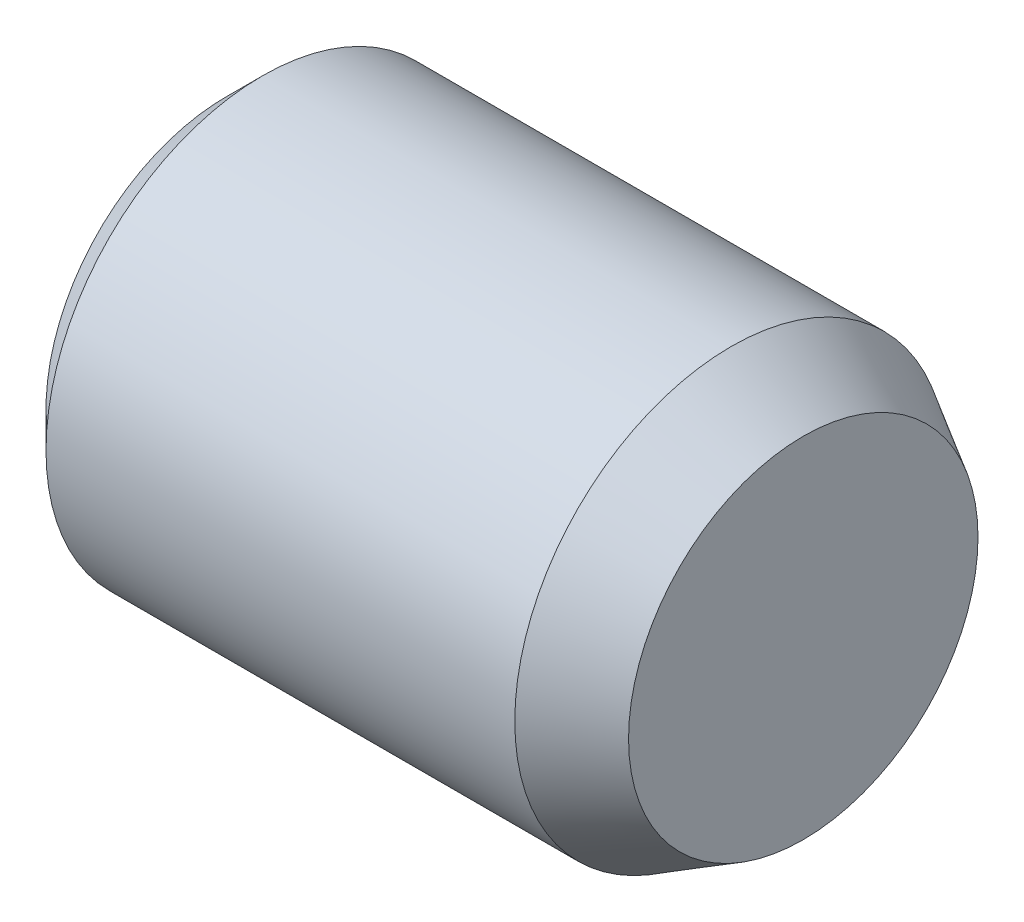
SolidWorks part; units mm, degrees
ref_plane "Přední rovina" through (0, 0, 0) normal (0, 0, 1) x (1, 0, 0)
ref_plane "Vrchní rovina" through (0, 0, 0) normal (0, 1, 0) x (1, 0, 0)
ref_plane "Pravá rovina" through (0, 0, 0) normal (1, 0, 0) x (0, 0, -1)
sketch "Skica1" plane through (0, 0, 0) normal (0, 1, 0) x (1, 0, 0)
  line L0 (0, 0) -> (0, 2.5)
  line L1 (0, 2.5) -> (0.5, 3)
  line L2 (0.5, 3) -> (7, 3)
  line L3 (7, 3) -> (8, 2.4226)
  line L4 (8, 2.4226) -> (8, 0)
  line L5 (8, 0) -> (0, 0) construction
  line L6 (0, 0) -> (8, 0)
  dimension "D1" = 45
  dimension "z2" = 0.5
  dimension "l" = 8
  dimension "D2" = 30
  dimension "z1" = 1
  dimension "M" = 6
revolve "Otočit kolem osy1" add sketch "Skica1" angle 360 about L5
cosmetic thread "Kosmetický závit1" parameters "D2"=5.1
hole_wizard "Díra1" positions "Skica3" profile "Skica2" legacy
sketch "Skica3" plane through (0, 0, 0) normal (-1, 0, 0) x (0, 0, 1)
  circle A0 centre (0, 0) radius 3 construction
  point P0 (0, 0)
sketch "Skica2" plane through (0, 0, 0) normal (0, 1, 0) x (0, 0, 1)
  line L0 (0, 0) -> (0, 5.0515)
  line L1 (0, 5.0515) -> (1.75, 4)
  line L2 (1.75, 4) -> (1.75, 0)
  line L4 (1.75, 0) -> (0, 0)
  line L6 (0, 5.0515) -> (-1.75, 4) construction
  line L7 (0, -4.2442) -> (0, 117.3081) construction
  dimension "Průměr" = 3.5
  dimension "Hloubka" = 4
  dimension "Úhel vrtání" = 118
sketch "Skica4" plane through (0, 0, 0) normal (-1, 0, 0) x (0, 0, 1)
  line L1 (-0.875, 1.5155) -> (-1.75, 0)
  line L2 (-1.75, 0) -> (-0.875, -1.5155)
  line L3 (-0.875, -1.5155) -> (0.875, -1.5155)
  line L4 (0.875, -1.5155) -> (1.75, 0)
  line L5 (1.75, 0) -> (0.875, 1.5155)
  line L6 (0.875, 1.5155) -> (-0.875, 1.5155)
  circle A0 centre (0, 0) radius 1.5155 construction
  circle A1 centre (0, 0) radius 1.75 construction
  circle M1 centre (0, 0) radius 1.75
extrude "Vysunout1" add sketch "Skica4" against normal up to next contours L1 M1 | L6 M1 | L5 M1 | L4 M1 | L3 M1 | L2 M1
sketch "Skica5" plane through (0, 0, 0) normal (0, 1, 0) x (1, 0, 0)
  line L0 (0, 1.75) -> (1.0104, 0)
  line L1 (1.0104, 0) -> (0, 0)
  line L3 (0, 0) -> (0, 1.75)
  dimension "D1" = 30
revolve "Odebrat otočením1" cut sketch "Skica5" angle 360 about L1
equation "\"D2@Kosmetický závit1\" = \"M@Skica1\" * 0.85"
